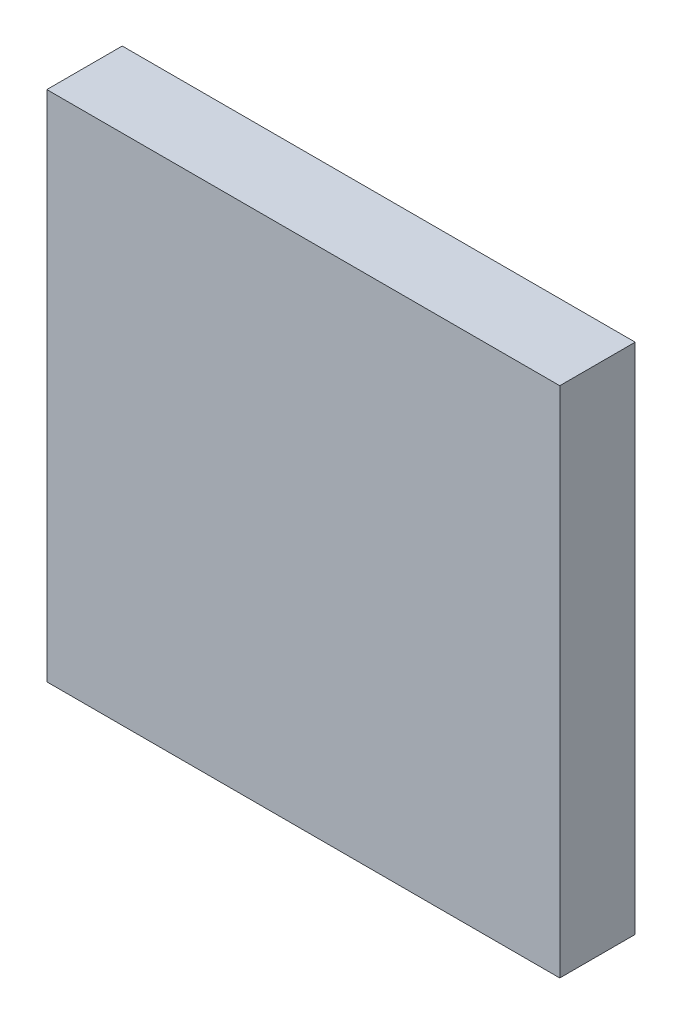
SolidWorks part; units mm, degrees
ref_plane "Front Plane" through (0, 0, 0) normal (0, 0, 1) x (1, 0, 0)
ref_plane "Top Plane" through (0, 0, 0) normal (0, 1, 0) x (1, 0, 0)
ref_plane "Right Plane" through (0, 0, 0) normal (1, 0, 0) x (0, 0, -1)
sketch "Sketch2" plane through (0, 0, 0) normal (0, 0, 1) x (1, 0, 0)
  line L1 (-17, 17) -> (17, 17)
  line L2 (-17, 17) -> (-17, -17)
  line L3 (-17, -17) -> (17, -17)
  line L4 (17, 17) -> (17, -17)
  line L5 (-17, 17) -> (17, -17) construction
  line L6 (-17, -17) -> (17, 17) construction
  point P0 (0, 0)
  dimension "D1" = 34
  dimension "D2" = 34
extrude "Boss-Extrude1" add sketch "Sketch2" along normal blind 5
